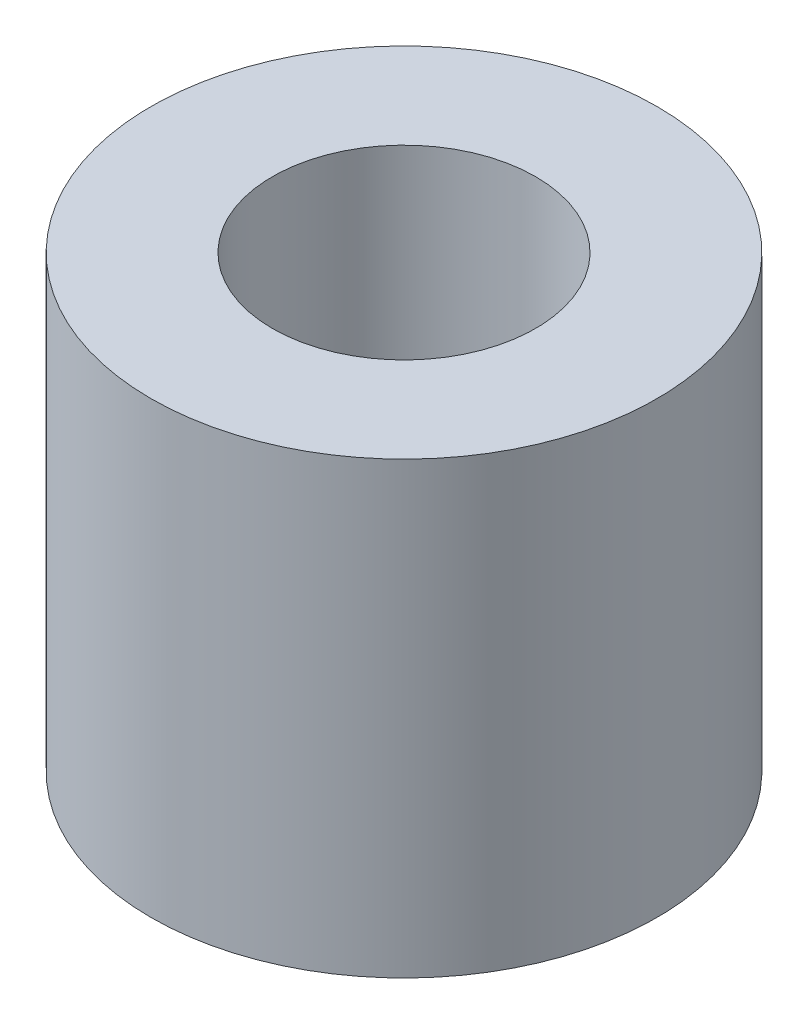
SolidWorks part; units mm, degrees
material "ABS"
ref_plane "前视基准面" through (0, 0, 0) normal (0, 0, 1) x (1, 0, 0)
ref_plane "上视基准面" through (0, 0, 0) normal (0, 1, 0) x (1, 0, 0)
ref_plane "右视基准面" through (0, 0, 0) normal (1, 0, 0) x (0, 0, -1)
other "Configuration Table"
sketch "草图1" plane through (0, 0, 0) normal (0, 1, 0) x (1, 0, 0)
  circle A0 centre (0, 0) radius 3.25
  circle A1 centre (0, 0) radius 6.25
  dimension "D1" = 6.5
  dimension "D2" = 3
extrude "凸台-拉伸1" add sketch "草图1" along normal blind 11.1
